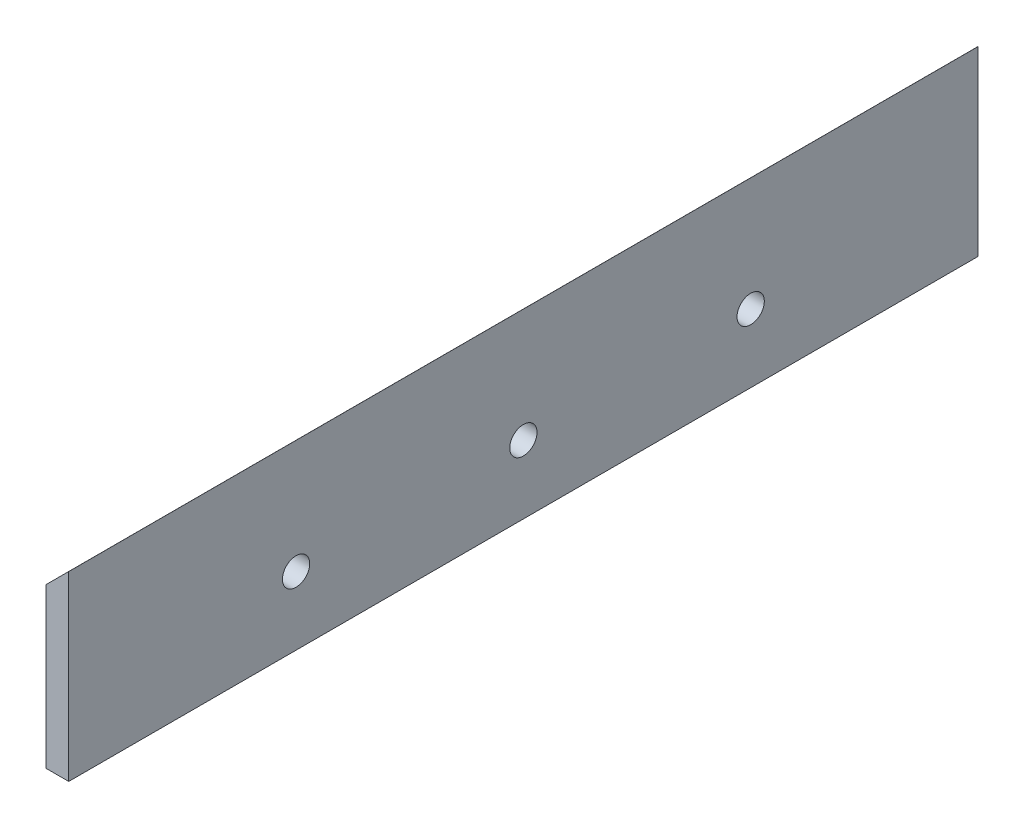
SolidWorks part; units mm, degrees
ref_plane "前基準面" through (0, 0, 0) normal (0, 0, 1) x (1, 0, 0)
ref_plane "上基準面" through (0, 0, 0) normal (0, 1, 0) x (1, 0, 0)
ref_plane "右基準面" through (0, 0, 0) normal (1, 0, 0) x (0, 0, -1)
sketch "草圖1" plane through (0, 0, 0) normal (0, 0, 1) x (1, 0, 0)
  line L0 (203.624, 1001.1769) -> (198.624, 1001.1769)
  line L1 (198.624, 1001.1769) -> (198.624, 1041.1769)
  line L7 (198.624, 1041.1769) -> (203.624, 1041.1629)
  line L8 (203.624, 1041.1629) -> (203.624, 1001.1769)
  dimension "D1" = 40
  dimension "D2" = 5
extrude "填料-伸長1" add sketch "草圖1" along normal blind 200
sketch "Sketch1" plane through (203.624, 0, 0) normal (1, 0, 0) x (0, 0, -1)
  line L0 (0, 1001.1769) -> (0, 1041.1629) construction
  line L1 (-200, 1001.1769) -> (0, 1001.1769) construction
  circle A0 centre (-50, 1016.1769) radius 3
  dimension "D1" = 6
  dimension "D2" = 50
  dimension "D3" = 15
chamfer "Chamfer1" distance 5 angle 45 1 edges at (198.624, 1041.1769, 100)
extrude "Cut-Extrude1" cut sketch "Sketch1" against normal up to surface (5 mm away) up to face at (198.624, 1018.6769, 100)
pattern_linear "LPattern1" count 3 spacing 50 along (0, 0, 1) of "Cut-Extrude1"
